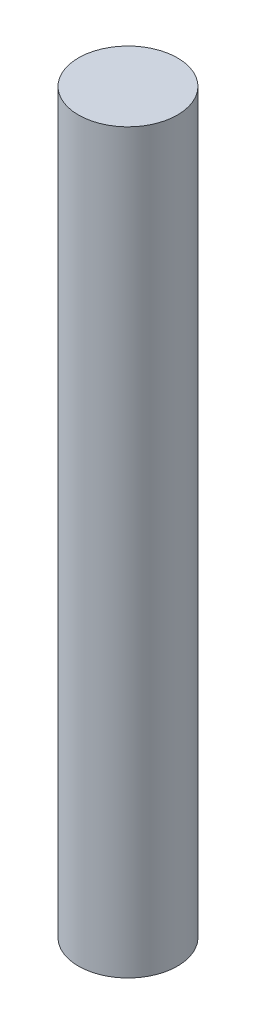
SolidWorks part; units mm, degrees
ref_plane "Front Plane" through (0, 0, 0) normal (0, 0, 1) x (1, 0, 0)
ref_plane "Top Plane" through (0, 0, 0) normal (0, 1, 0) x (1, 0, 0)
ref_plane "Right Plane" through (0, 0, 0) normal (1, 0, 0) x (0, 0, -1)
sketch "Sketch1" plane through (0, 0, 0) normal (0, 1, 0) x (1, 0, 0)
  circle A0 centre (-36.3262, 11.3461) radius 4.5
  dimension "D1" = 9
extrude "Boss-Extrude1" add sketch "Sketch1" along normal blind 67
